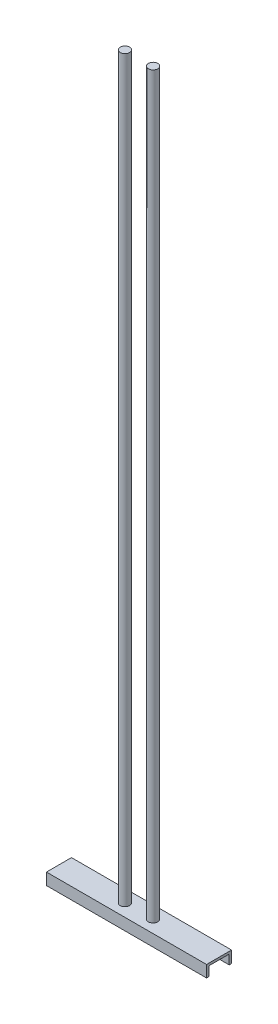
SolidWorks part; units mm, degrees
ref_plane "Alzado" through (0, 0, 0) normal (0, 0, 1) x (1, 0, 0)
ref_plane "Planta" through (0, 0, 0) normal (0, 1, 0) x (1, 0, 0)
ref_plane "Vista lateral" through (0, 0, 0) normal (1, 0, 0) x (0, 0, -1)
sketch "Croquis2" plane through (0, 0, 0) normal (0, 1, 0) x (1, 0, 0)
  line L1 (-325, -50.8) -> (325, -50.8)
  line L2 (-325, -50.8) -> (-325, 50.8)
  line L3 (-325, 50.8) -> (325, 50.8)
  line L4 (325, -50.8) -> (325, 50.8)
  line L5 (-325, -50.8) -> (325, 50.8) construction
  line L6 (-325, 50.8) -> (325, -50.8) construction
  point P0 (0, 0)
  dimension "D1" = 101.6
  dimension "D2" = 650
extrude "Saliente-Extruir1" add sketch "Croquis2" against normal blind 9.525
sketch "Croquis3" plane through (0, -9.525, 0) normal (0, -1, 0) x (1, 0, 0)
  line L0 (325, 50.8) -> (325, -50.8) construction
  line L1 (-325, 50.8) -> (325, 50.8)
  line L2 (-325, 50.8) -> (-325, 41.275)
  line L3 (-325, 41.275) -> (325, 41.275)
  line L4 (325, 50.8) -> (325, 41.275)
  line L5 (-325, -50.8) -> (-325, 50.8) construction
  line L6 (325, -50.8) -> (-325, -50.8)
  line L7 (325, -50.8) -> (325, -41.275)
  line L8 (325, -41.275) -> (-325, -41.275)
  line L9 (-325, -50.8) -> (-325, -41.275)
  dimension "D1" = 9.525
  dimension "D2" = 9.525
extrude "Saliente-Extruir2" add sketch "Croquis3" along normal blind 38.1
fillet "Redondeo1" radius 5 2 edges at (0, -9.525, -41.275) (0, -9.525, 41.275)
sketch "Croquis4" plane through (0, 0, 0) normal (0, 1, 0) x (1, 0, 0)
  line L0 (0, 0) -> (-57.15, 0) construction
  line L2 (0, 0) -> (0, 50.8) construction
  line L3 (325, 50.8) -> (-325, 50.8) construction
  circle A0 centre (-57.15, 0) radius 19.05
  circle A1 centre (57.15, 0) radius 19.05
  dimension "D2" = 38.1
  dimension "D1" = 57.15
extrude "Saliente-Extruir3" add sketch "Croquis4" along normal blind 3000
